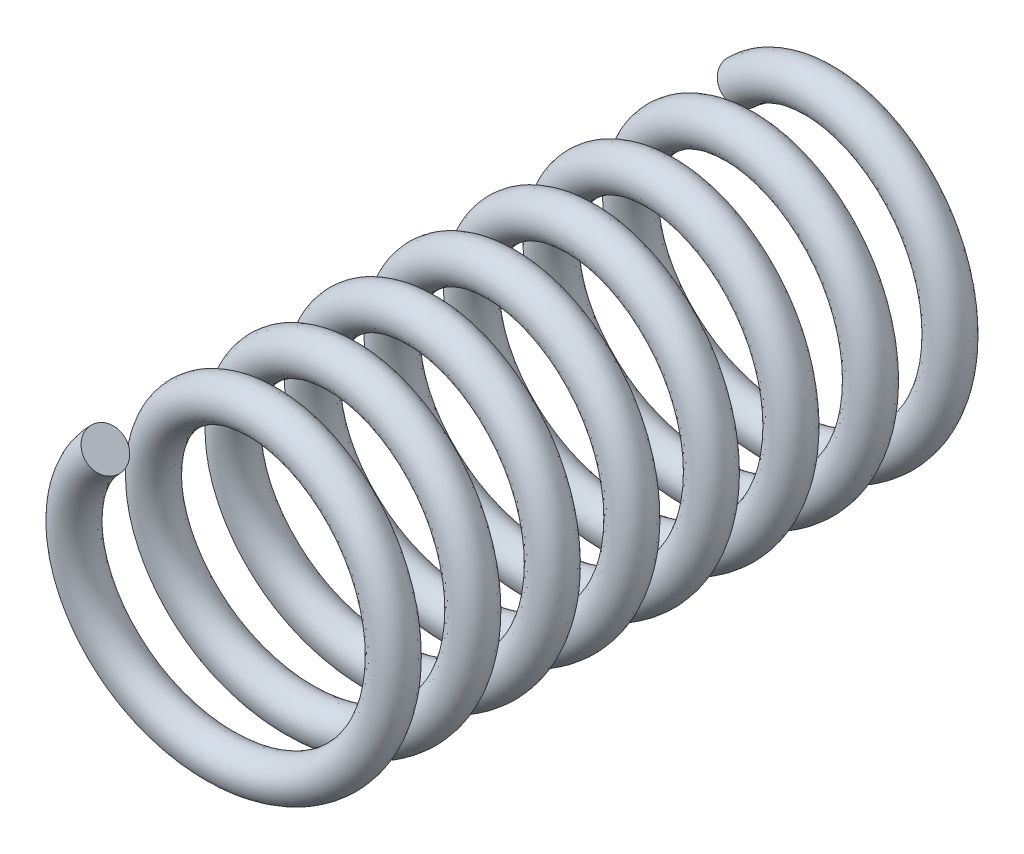
SolidWorks part; units mm, degrees
material "SS BS EN 10088-2 1.4301"
ref_plane "Front" through (0, 0, 0) normal (0, 0, 1) x (1, 0, 0)
ref_plane "Top" through (0, 0, 0) normal (0, 1, 0) x (1, 0, 0)
ref_plane "Right" through (0, 0, 0) normal (1, 0, 0) x (0, 0, -1)
sketch "Sketch1" plane through (0, 0, 0) normal (0, 0, 1) x (1, 0, 0)
  circle A0 centre (0, 0) radius 1.75
  dimension "D1" = 3.5
curve "Helix/Spiral1" pitch 1 height 8 turns 8
sketch "Sketch2" plane through (0, 0, 0) normal (1, 0, 0) x (0, 0, -1)
  circle A0 centre (-6.625, -1.75) radius 0.25
  dimension "D1" = 0.5
sweep "Sweep1" add profiles "Sketch2" path "Helix/Spiral1"
